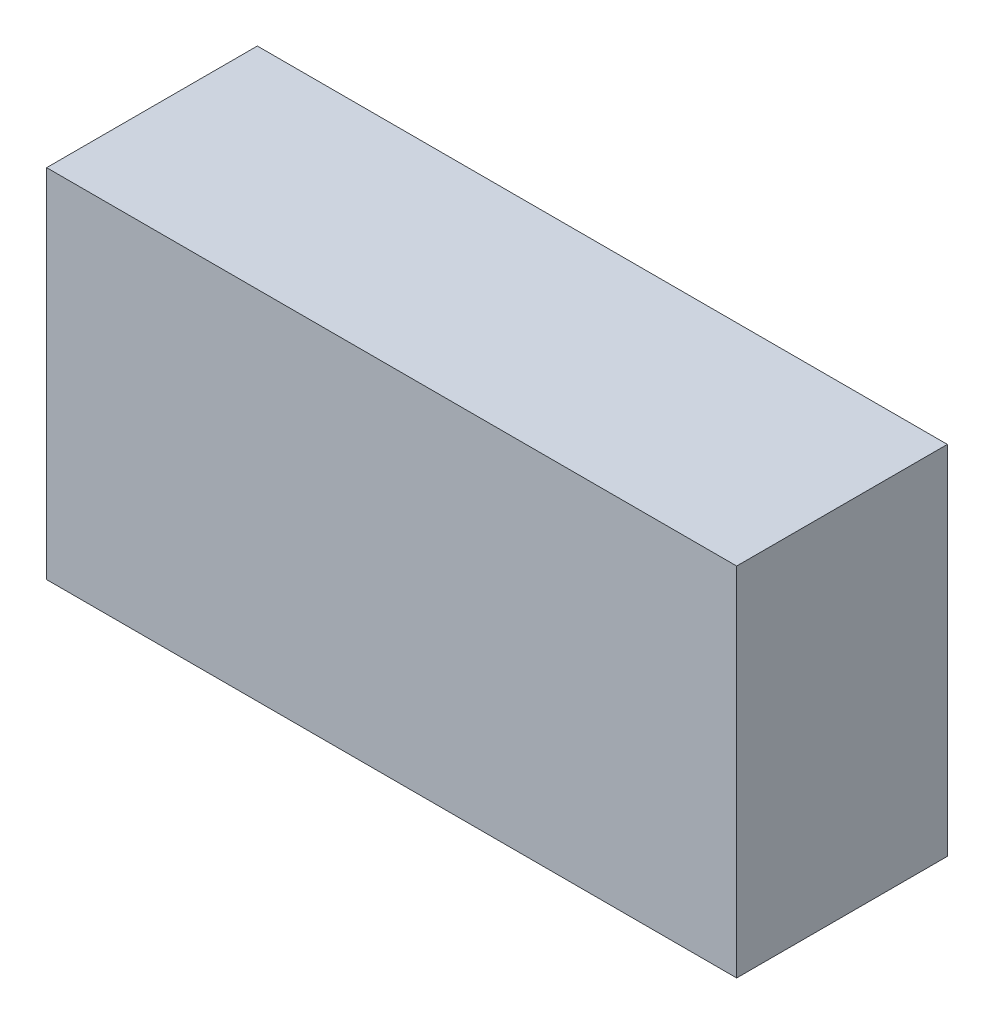
SolidWorks part; units mm, degrees
ref_plane "Front Plane" through (0, 0, 0) normal (0, 0, 1) x (1, 0, 0)
ref_plane "Top Plane" through (0, 0, 0) normal (0, 1, 0) x (1, 0, 0)
ref_plane "Right Plane" through (0, 0, 0) normal (1, 0, 0) x (0, 0, -1)
sketch "Sketch1" plane through (0, 0, 0) normal (0, 1, 0) x (1, 0, 0)
  line L1 (-9.825, 3) -> (9.825, 3)
  line L2 (-9.825, 3) -> (-9.825, -3)
  line L3 (-9.825, -3) -> (9.825, -3)
  line L4 (9.825, 3) -> (9.825, -3)
  line L5 (-9.825, 3) -> (9.825, -3) construction
  line L6 (-9.825, -3) -> (9.825, 3) construction
  point P0 (0, 0)
  dimension "D1" = 6
  dimension "D2" = 19.65
extrude "Boss-Extrude1" add sketch "Sketch1" along normal blind 10.16
sketch "Sketch2" plane through (0, 0, 0) normal (0, -1, 0) x (1, 0, 0)
  line L0 (0, -3) -> (0, -2.1) construction
  line L1 (9.825, -3) -> (-9.825, -3) construction
  line L2 (0, -2.1) -> (0.005, -2.1) construction
  line L3 (0.005, -2.1) -> (2.545, -2.1) construction
  line L4 (2.545, -2.1) -> (5.085, -2.1) construction
  line L5 (0.005, -2.1) -> (-5.075, -2.1) construction
  line L6 (-5.075, -2.1) -> (-7.615, -2.1) construction
  line L7 (-9.825, -3) -> (-9.825, 3) construction
  circle A0 centre (0.005, -2.1) radius 0.25
  circle A1 centre (2.545, -2.1) radius 0.25
  circle A2 centre (5.085, -2.1) radius 0.25
  circle A3 centre (-5.075, -2.1) radius 0.25
  circle A4 centre (-7.615, -2.1) radius 0.25
  dimension "D2" = 0.005
  dimension "D3" = 0.5
  dimension "D1" = 0.9
  dimension "D4" = 2.21
  dimension "D5" = 2.54
  dimension "D6" = 2.54
  dimension "D7" = 2.54
extrude "Boss-Extrude2" add sketch "Sketch2" along normal blind 4.1
